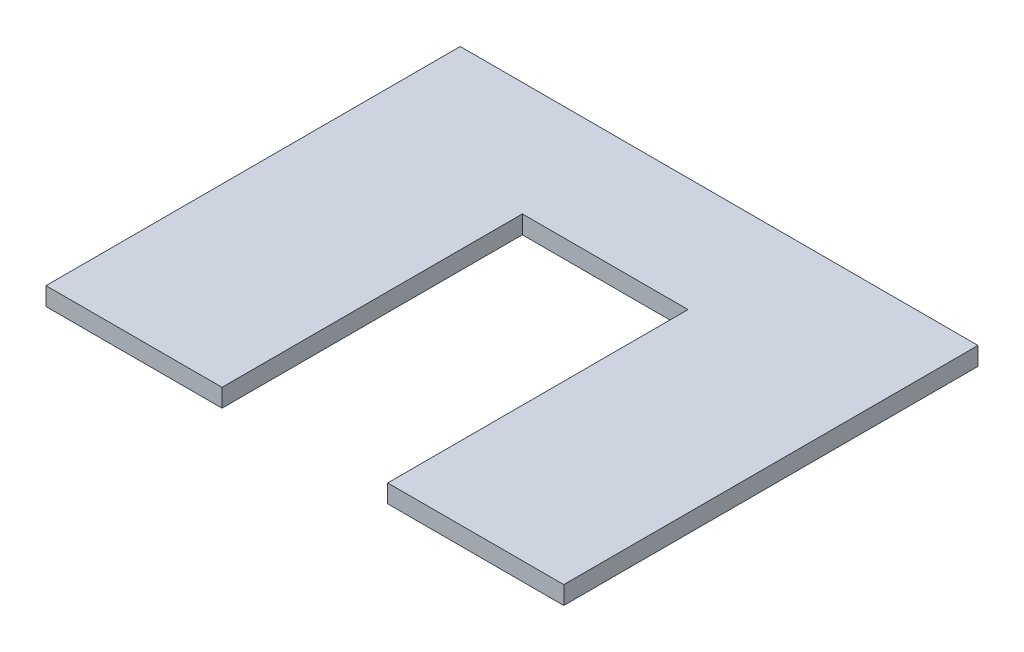
SolidWorks part; units mm, degrees
material "AISI 316 Stainless Steel Sheet (SS)"
ref_plane "Front Plane" through (0, 0, 0) normal (0, 0, 1) x (1, 0, 0)
ref_plane "Top Plane" through (0, 0, 0) normal (0, 1, 0) x (1, 0, 0)
ref_plane "Right Plane" through (0, 0, 0) normal (1, 0, 0) x (0, 0, -1)
sketch "Sketch1" plane through (0, 0, 0) normal (0, 1, 0) x (1, 0, 0)
  line L0 (17, -40) -> (17, -11)
  line L1 (0, 0) -> (50, 0)
  line L2 (0, 0) -> (0, -40)
  line L3 (0, -40) -> (17, -40)
  line L4 (50, 0) -> (50, -40)
  line L5 (17, -11) -> (33, -11)
  line L6 (33, -11) -> (33, -40)
  line L8 (33, -40) -> (50, -40)
  circle A0 centre (25, -15) radius 1 construction
  point P8 (25, 0)
  point P12 (0, 0)
  point P13 (18.0655, -60.3048)
  point P14 (33.6927, -57.0591)
  point P15 (0, 0)
  point P16 (0, 0)
  point P17 (35.8565, -50)
  dimension "D2" = 2
  dimension "D1" = 50
  dimension "D3" = 15
  dimension "D4" = 40
  dimension "D5" = 4
  dimension "D6" = 16
extrude "Boss-Extrude1" add sketch "Sketch1" along normal blind 1.75
